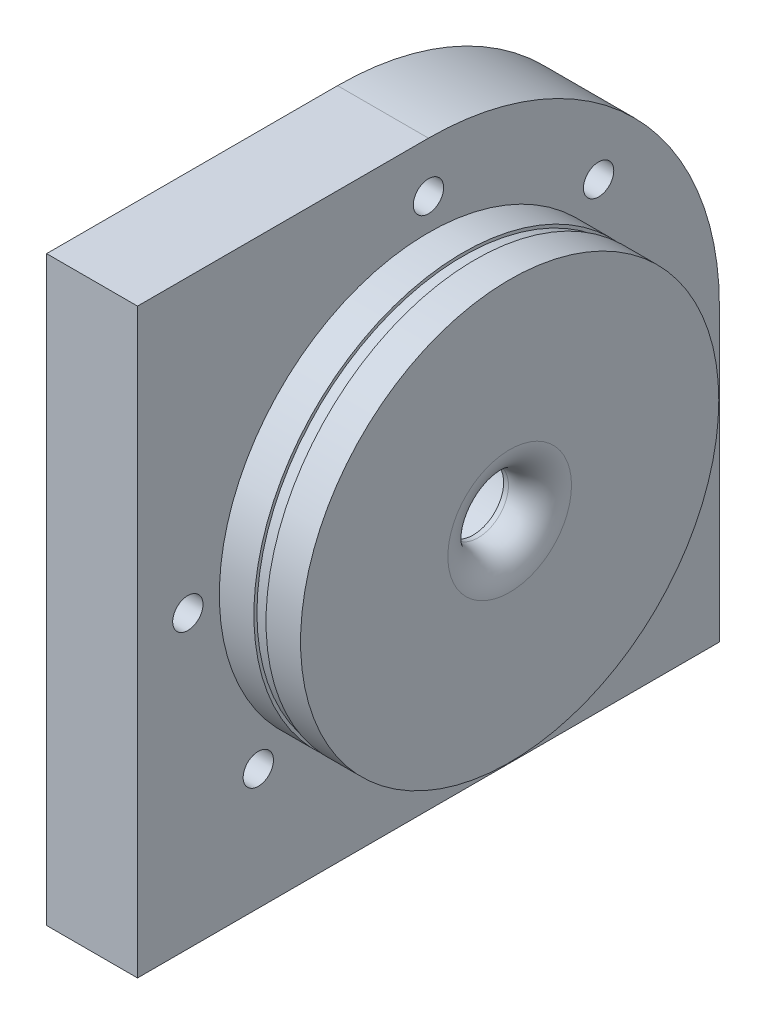
SolidWorks part; units mm, degrees
ref_plane "Front Plane" through (0, 0, 0) normal (0, 0, 1) x (1, 0, 0)
ref_plane "Top Plane" through (0, 0, 0) normal (0, 1, 0) x (1, 0, 0)
ref_plane "Right Plane" through (0, 0, 0) normal (1, 0, 0) x (0, 0, -1)
sketch "Sketch1" plane through (0, 0, 0) normal (1, 0, 0) x (0, 0, -1)
  circle A0 centre (0, 0) radius 43.815
extrude "Housing Fitting Extrude" add sketch "Sketch1" along normal blind 17.018
sketch "Sketch2" plane through (0, 0, 0) normal (-1, 0, 0) x (0, 0, 1)
  line L0 (60.96, 0) -> (60.96, 60.96)
  line L1 (60.96, 60.96) -> (0, 60.96)
  line L2 (60.96, 0) -> (60.96, -54.61)
  line L3 (60.96, -60.96) -> (-60.96, -60.96)
  line L7 (0, -55) -> (0, 55) construction
  line L11 (-60.96, 0) -> (-60.96, -54.61)
  line L12 (60.96, -60.96) -> (60.96, -54.61)
  line L13 (-60.96, -60.96) -> (-60.96, -54.61)
  arc A0 (0, 60.96) -> (-60.96, 0) centre (0, 0) ccw
extrude "Housing Body 1" add sketch "Sketch2" along normal blind 19.05 contours A0 L11 L13 L3 L12 L2 L0 L1
sketch "Sketch3" plane through (17.018, 0, 0) normal (1, 0, 0) x (0, 0, -1)
  circle A0 centre (0, 0) radius 6.35
extrude "Impeller Bore" cut sketch "Sketch3" against normal blind 17.018
sketch "Sketch4" plane through (0, 0, 0) normal (1, 0, 0) x (0, 0, -1)
  circle A0 centre (0, 0) radius 4
extrude "Shaft Bore" cut sketch "Sketch4" against normal blind 70.612
ref_plane "O-Ring Sketch Plane" through (8.509, 0, 0) normal (1, 0, 0) x (0, 0, -1)
sketch "Sketch5" plane through (8.509, 0, 0) normal (1, 0, 0) x (0, 0, -1)
  circle A0 centre (0, 0) radius 43.942
  circle A1 centre (0, 0) radius 43.18
extrude "O-Ring Cut" cut sketch "Sketch5" against normal blind 1.27 and the other way blind 1.27
sketch "Sketch8" plane through (-19.05, 0, 0) normal (-1, 0, 0) x (0, 0, 1)
  circle A1 centre (52.959, 0) radius 3.175
extrude "Fastening Bore" [suppressed] cut sketch "Sketch8" against normal blind 19.05
sketch "Sketch10" plane through (0, 0, 60.96) normal (0, 0, 1) x (1, 0, 0)
  line L0 (0, -60.96) -> (0, 60.96) construction
  line L1 (-19.05, 60.96) -> (0, 60.96)
  line L2 (-19.05, 60.96) -> (-19.05, 10.16)
  line L3 (-19.05, 10.16) -> (0, 10.16)
  line L4 (0, 60.96) -> (0, 10.16)
extrude "Discharge Cut" [suppressed] cut sketch "Sketch10" against normal blind 10.541
sketch "Sketch12" plane through (0, 0, 0) normal (1, 0, 0) x (0, 0, -1)
  circle A0 centre (-50.419, 0) radius 3.175
extrude "Cut-Extrude2" cut sketch "Sketch12" against normal blind 19.05
pattern_circular "CirPattern1" count 8 over 360 about axis through (0, 0, 0) along (1, 0, 0) skipping 7 of "Cut-Extrude2"
sketch "Sketch13" plane through (0, 0, 60.96) normal (0, 0, 1) x (1, 0, 0)
  circle A1 centre (-9.525, -41.8177) radius 3.175
extrude "Cut-Extrude3" [suppressed] cut sketch "Sketch13" against normal blind 16.51
sketch "Sketch14" plane through (0, -60.96, 0) normal (0, -1, 0) x (1, 0, 0)
  circle A0 centre (-9.525, -46.7543) radius 3.175
  circle A1 centre (-9.525, 41.9141) radius 3.3928
extrude "Cut-Extrude4" cut sketch "Sketch14" against normal blind 16.51
sketch "Sketch15" plane through (0, 0, -60.96) normal (0, 0, -1) x (-1, 0, 0)
  circle A0 centre (9.525, -39.3375) radius 3.175
extrude "Cut-Extrude5" cut sketch "Sketch15" against normal blind 10.922
fillet "Fillet1" radius 6.604 1 edges at (17.018, 0, -6.35)
sketch "Sketch16" plane through (-19.05, 0, 0) normal (-1, 0, 0) x (0, 0, 1)
  circle A0 centre (0, 0) radius 12.954
extrude "Cut-Extrude7" cut sketch "Sketch16" against normal blind 28.448
sketch "Sketch17" plane through (-19.05, 0, 0) normal (-1, 0, 0) x (0, 0, 1)
  circle A0 centre (0, 0) radius 15.24
extrude "Cut-Extrude8" cut sketch "Sketch17" against normal blind 13.97
sketch "Sketch18" plane through (0, 60.96, 0) normal (0, 1, 0) x (1, 0, 0)
  circle A0 centre (-13.4538, -7.8664) radius 0.7265
extrude "Cut-Extrude9" [suppressed] cut sketch "Sketch18" against normal blind 58.166
sketch "Sketch19" plane through (0, 60.96, 0) normal (0, 1, 0) x (1, 0, 0)
  circle A0 centre (-13.2089, -8.2248) radius 4.7625
extrude "Cut-Extrude10" [suppressed] cut sketch "Sketch19" against normal blind 7.62
sketch "Sketch20" plane through (-19.05, 0, 0) normal (-1, 0, 0) x (0, 0, 1)
  circle A0 centre (0, 0) radius 25.146
extrude "Cut-Extrude11" cut sketch "Sketch20" against normal blind 6.35
